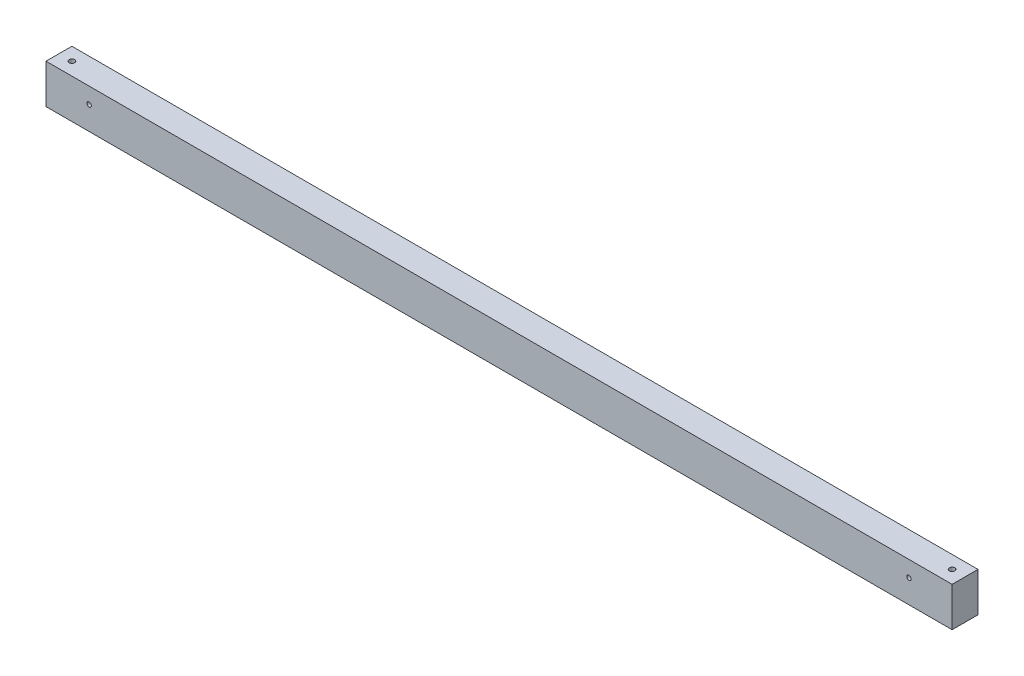
SolidWorks part; units mm, degrees
ref_plane "Front Plane" through (0, 0, 0) normal (0, 0, 1) x (1, 0, 0)
ref_plane "Top Plane" through (0, 0, 0) normal (0, 1, 0) x (1, 0, 0)
ref_plane "Right Plane" through (0, 0, 0) normal (1, 0, 0) x (0, 0, -1)
sketch "Sketch1" plane through (0, 0, 0) normal (0, 1, 0) x (1, 0, 0)
  line L1 (-1050, 60) -> (1050, 60)
  line L2 (-1050, 60) -> (-1050, 0)
  line L3 (-1050, 0) -> (1050, 0)
  line L4 (1050, 60) -> (1050, 0)
  dimension "D1" = 2100
  dimension "D2" = 60
extrude "Boss-Extrude1" add sketch "Sketch1" along normal blind 91.2
sketch "Sketch2" plane through (0, 0, 0) normal (0, 0, 1) x (1, 0, 0)
  line L2 (-1050, 0) -> (1050, 0) construction
  line L3 (0, 0) -> (0, 91.2) construction
  line L4 (-1050, 91.2) -> (1050, 91.2) construction
  circle A0 centre (-950, 54.25) radius 5.1
  circle A1 centre (950, 54.25) radius 5.1
  dimension "D1" = 10.2
  dimension "D3" = 54.25
  dimension "D2" = 950
extrude "Cut-Extrude1" cut sketch "Sketch2" against normal through all from surface at 0 starting at face at (0, 45.6, 0)
sketch "Sketch3" plane through (0, 0, 0) normal (0, 1, 0) x (1, 0, 0)
  line L0 (-1050, 0) -> (1050, 0) construction
  line L1 (1050, 0) -> (1050, 60) construction
  line L2 (0, 0) -> (0, 60) construction
  line L3 (1050, 60) -> (-1050, 60) construction
  circle A0 centre (1020, 30) radius 6.35
  circle A1 centre (-1020, 30) radius 6.35
  dimension "D3" = 12.7
  dimension "D1" = 30
  dimension "D2" = 30
extrude "Cut-Extrude2" cut sketch "Sketch3" against normal up to surface (91.2 mm away) from surface at 91.2 up to face at (0, 0, -30) starting at face at (0, 91.2, -30)
equation "\"absorber_plate_width\" = 1000mm"
equation "\"absorber_plate_length\" = 2000mm"
equation "\"absorber_plate_thickness\" = 4mm"
equation "\"groove_depth\" = 10mm"
equation "\"frame_thickness\" = 60mm"
equation "\"insulation_thickness\" = 50mm"
equation "\"D2@Sketch1\"=\"frame_thickness\""
equation "\"glass_thickness\" = 3mm"
equation "\"pipe_distances\" = 100mm"
equation "\"pipe_OD\" = 8.5mm"
equation "\"pipe_ID\" = 7.8mm"
equation "\"pipe_straight_length\" = 850mm"
equation "\"absorber_to_glass\" = 25mm"
equation "\"D2@Sketch2\"=(\"absorber_plate_length\"-\"pipe_distances\")/2"
equation "\"D1@Sketch2\"=\"pipe_OD\"*1.2"
equation "\"D3@Sketch2\"=\"insulation_thickness\"+\"pipe_OD\"/2"
equation "\"D1@Sketch1\"=\"absorber_plate_length\"+\"frame_thickness\"*2-\"groove_depth\"*2"
equation "\"D1@Boss-Extrude1\"=\"insulation_thickness\"+\"pipe_OD\"+\"absorber_plate_thickness\"*1.1+\"absorber_to_glass\"+\"glass_thickness\"*1.1"
